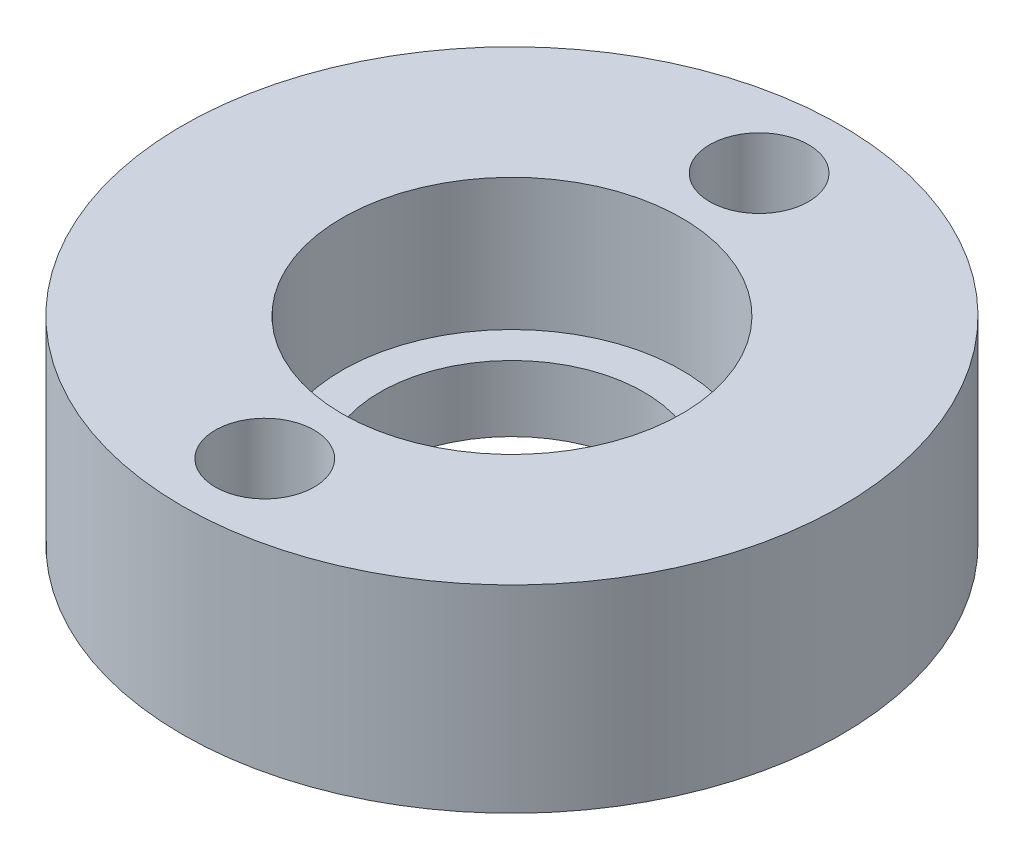
SolidWorks part; units mm, degrees
ref_plane "Спереди" through (0, 0, 0) normal (0, 0, 1) x (1, 0, 0)
ref_plane "Сверху" through (0, 0, 0) normal (0, 1, 0) x (1, 0, 0)
ref_plane "Справа" through (0, 0, 0) normal (1, 0, 0) x (0, 0, -1)
sketch "Эскиз1" plane through (0, 0, 0) normal (0, 1, 0) x (1, 0, 0)
  circle A0 centre (0, 0) radius 10
  circle A1 centre (0, 0) radius 7.5 construction
  circle A2 centre (0, 7.5) radius 1.5
  circle A3 centre (0, 0) radius 9 construction
  circle A5 centre (0, -7.5) radius 1.5
  circle A7 centre (0, 0) radius 4
  dimension "D1" = 20
  dimension "D2" = 18
  dimension "D3" = 15
  dimension "D4" = 8
extrude "Бобышка-Вытянуть1" add sketch "Эскиз1" along normal blind 6
sketch "Эскиз2" plane through (0, 6, 0) normal (0, 1, 0) x (1, 0, 0)
  circle A0 centre (0, 0) radius 5.15
extrude "Вырез-Вытянуть1" cut sketch "Эскиз2" against normal blind 4
